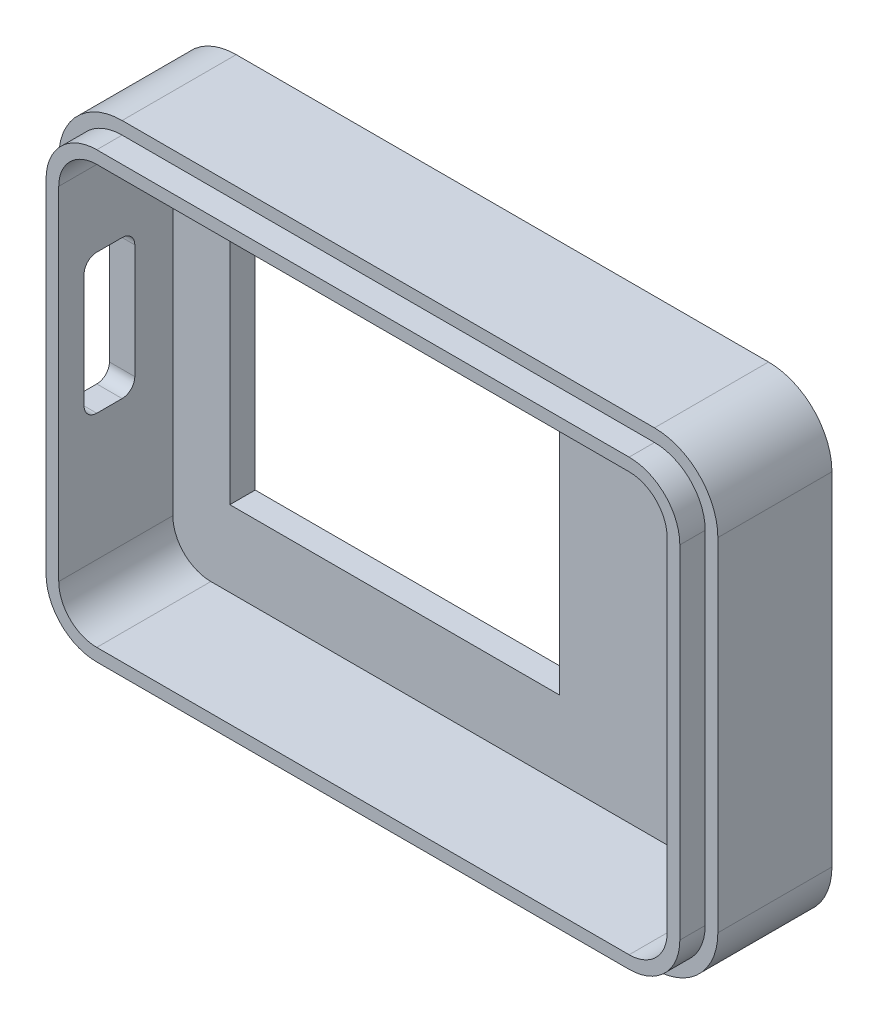
SolidWorks part; units mm, degrees
ref_plane "Plan de face" through (0, 0, 0) normal (0, 0, 1) x (1, 0, 0)
ref_plane "Plan de dessus" through (0, 0, 0) normal (0, 1, 0) x (1, 0, 0)
ref_plane "Plan de droite" through (0, 0, 0) normal (1, 0, 0) x (0, 0, -1)
sketch "Esquisse1" plane through (0, 0, 0) normal (0, 0, 1) x (1, 0, 0)
  line L1 (5, 0) -> (47, 0)
  line L2 (0, 5) -> (0, 32)
  line L3 (5, 37) -> (47, 37)
  line L4 (52, 5) -> (52, 32)
  arc A0 (47, 37) -> (52, 32) centre (47, 32) cw
  arc A1 (47, 0) -> (52, 5) centre (47, 5) ccw
  arc A2 (5, 0) -> (0, 5) centre (5, 5) cw
  arc A3 (0, 32) -> (5, 37) centre (5, 32) cw
  point P9 (52, 0)
  point P12 (0, 0)
  point P15 (0, 37)
  dimension "D3" = 5
  dimension "D1" = 37
  dimension "D2" = 52
extrude "Boss.-Extru.1" add sketch "Esquisse1" along normal blind 11
shell "Coque5" thickness 2
sketch "Esquisse5" plane through (0, 0, 2) normal (0, 0, 1) x (1, 0, 0)
  line L0 (5, 2) -> (47, 2) construction
  line L1 (6.5, 26) -> (32.5, 26)
  line L2 (6.5, 26) -> (6.5, 8)
  line L3 (6.5, 8) -> (32.5, 8)
  line L4 (32.5, 26) -> (32.5, 8)
  line L5 (2, 32) -> (2, 5) construction
  line L7 (32.5, 26) -> (-4.574, 26) construction
  dimension "D1" = 26
  dimension "D2" = 18
  dimension "D3" = 4.5
  dimension "D4" = 6
extrude "Enlèv. mat.-Extru.4" cut sketch "Esquisse5" against normal through all
sketch "Esquisse6" plane through (0, 0, 11) normal (0, 0, 1) x (1, 0, 0)
  line L8 (47, 36) -> (5, 36)
  line L9 (1, 32) -> (1, 5)
  line L10 (5, 1) -> (47, 1)
  line L11 (51, 5) -> (51, 32)
  line L12 (47, 36) -> (5, 36)
  line L13 (1, 32) -> (1, 5)
  line L14 (5, 1) -> (47, 1)
  line L15 (51, 5) -> (51, 32)
  arc A8 (51, 32) -> (47, 36) centre (47, 32) ccw
  arc A9 (5, 36) -> (1, 32) centre (5, 32) ccw
  arc A10 (1, 5) -> (5, 1) centre (5, 5) ccw
  arc A11 (47, 1) -> (51, 5) centre (47, 5) ccw
  arc A12 (51, 32) -> (47, 36) centre (47, 32) ccw
  arc A13 (5, 36) -> (1, 32) centre (5, 32) ccw
  arc A14 (1, 5) -> (5, 1) centre (5, 5) ccw
  arc A15 (47, 1) -> (51, 5) centre (47, 5) ccw
  dimension "D1" = 1
extrude "Enlèv. mat.-Extru.5" cut sketch "Esquisse6" against normal blind 2 flip side to cut
sketch "Esquisse7" plane through (0, 0, 0) normal (-1, 0, 0) x (0, 0, 1)
  line L0 (11, 32) -> (11, 5) construction
  line L1 (6, 26) -> (8, 26)
  line L2 (5, 25) -> (5, 16)
  line L3 (6, 15) -> (8, 15)
  line L4 (9, 25) -> (9, 16)
  line L5 (9, 5) -> (0, 5) construction
  arc A0 (6, 26) -> (5, 25) centre (6, 25) ccw
  arc A1 (8, 26) -> (9, 25) centre (8, 25) cw
  arc A2 (5, 16) -> (6, 15) centre (6, 16) ccw
  arc A3 (8, 15) -> (9, 16) centre (8, 16) ccw
  point P8 (5, 26)
  point P11 (9, 26)
  point P14 (5, 15)
  dimension "D4" = 1
  dimension "D1" = 4
  dimension "D2" = 11
  dimension "D3" = 2
  dimension "D5" = 10
extrude "Enlèv. mat.-Extru.6" cut sketch "Esquisse7" against normal blind 10 contours A3 L3 A2 L2 A0 L1 A1 L4
sketch "Esquisse8" plane through (0, 0, 2) normal (0, 0, 1) x (1, 0, 0)
